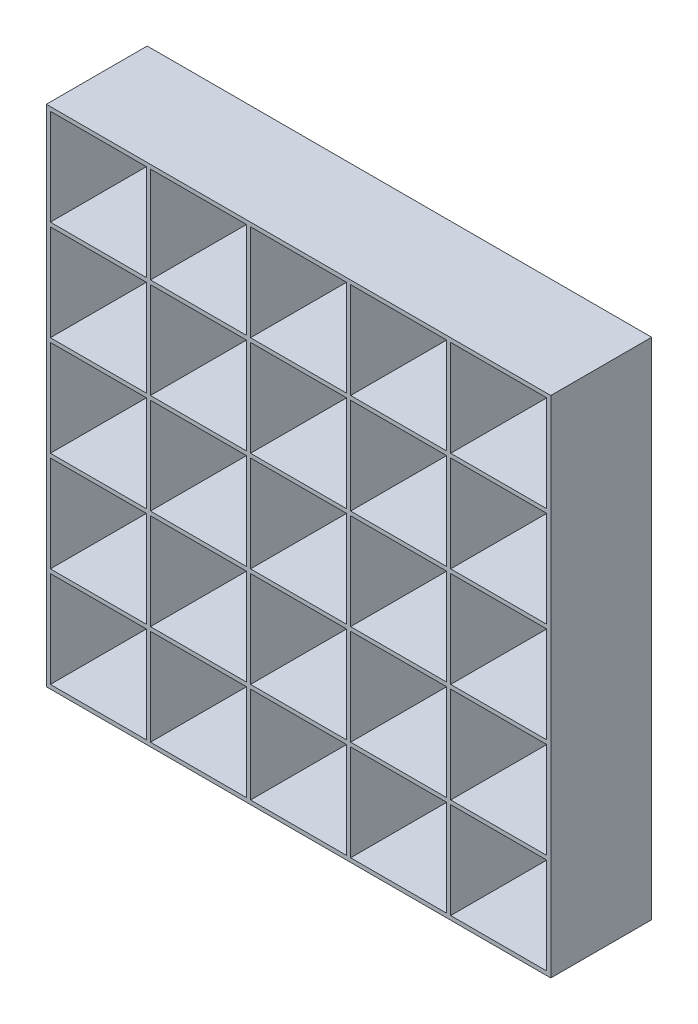
SolidWorks part; units mm, degrees
ref_plane "Front Plane" through (0, 0, 0) normal (0, 0, 1) x (1, 0, 0)
ref_plane "Top Plane" through (0, 0, 0) normal (0, 1, 0) x (1, 0, 0)
ref_plane "Right Plane" through (0, 0, 0) normal (1, 0, 0) x (0, 0, -1)
sketch "Sketch1" plane through (0, 0, 0) normal (0, 0, 1) x (1, 0, 0)
  line L1 (1250, 1250) -> (-1250, 1250)
  line L2 (1250, 1250) -> (1250, -1250)
  line L3 (1250, -1250) -> (-1250, -1250)
  line L4 (-1250, 1250) -> (-1250, -1250)
  line L5 (1250, 1250) -> (-1250, -1250) construction
  line L6 (1250, -1250) -> (-1250, 1250) construction
  line L7 (-1250, 1250) -> (-1230, 1250)
  line L8 (-1250, 1250) -> (-1250, -1250)
  line L9 (-1250, -1250) -> (-1230, -1250)
  line L10 (-1230, 1250) -> (-1230, -1250)
  point P0 (0, 0)
  dimension "D1" = 2500
  dimension "D2" = 2500
  dimension "D3" = 20
extrude "Boss-Extrude1" add sketch "Sketch1" along normal blind 500 contours L4 L3 L2 L1
sketch "Sketch3" plane through (0, 0, 500) normal (0, 0, 1) x (1, 0, 0)
  line L0 (-734, -1170.8048) -> (-734, -1230)
  line L109 (-1230, 1230) -> (-1230, 754)
  line L117 (-734, -238) -> (-258, -238)
  line L120 (-1230, 1230) -> (-754, 1230)
  line L126 (1230, 1230) -> (1230, 754)
  line L130 (-734, -1230) -> (-258, -1230)
  line L132 (-1230, 1230) -> (-754, 1230)
  line L133 (-1230, 1230) -> (-1230, 754)
  line L134 (-1230, 754) -> (-754, 754)
  line L135 (-754, 1230) -> (-754, 774.8128)
  line L137 (-754, 1230) -> (-754, 754)
  line L139 (-734, 1230) -> (-734, 754)
  line L140 (-1230, 754) -> (-754, 754)
  line L142 (-1230, 734) -> (-754, 734)
  line L144 (-1230, 734) -> (-754, 734)
  line L145 (-1230, 734) -> (-1230, 258)
  line L146 (-1230, 258) -> (-754, 258)
  line L147 (-754, 734) -> (-754, 258)
  line L148 (-1230, 258) -> (-754, 258)
  line L150 (-1230, 238) -> (-754, 238)
  line L152 (-1230, 238) -> (-754, 238)
  line L153 (-1230, 238) -> (-1230, -238)
  line L154 (-1230, -238) -> (-751.9983, -238)
  line L155 (-754, 238) -> (-754, -238)
  line L156 (-1230, -258) -> (-754, -258)
  line L158 (-1230, -258) -> (-754, -258)
  line L159 (-1230, -258) -> (-1230, -734)
  line L160 (-1230, -734) -> (-754, -734)
  line L161 (-754, -258) -> (-754, -734)
  line L162 (-1230, -734) -> (-754, -734)
  line L164 (-1230, -754) -> (-754, -754)
  line L166 (-1230, -754) -> (-754, -754)
  line L167 (-1230, -754) -> (-1230, -1230)
  line L168 (-1230, -1230) -> (-754, -1230)
  line L169 (-754, -754) -> (-754, -1230)
  line L170 (-734, 734) -> (-258, 734)
  line L171 (-734, 1230) -> (-258, 1230)
  line L172 (-734, 1230) -> (-734, 754)
  line L173 (-734, 754) -> (-258, 754)
  line L174 (-258, 1230) -> (-258, 754)
  line L176 (-258, 1230) -> (-258, 754)
  line L178 (-238, 1230) -> (-238, 754)
  line L179 (-238, 1230) -> (238, 1230)
  line L180 (-238, 1230) -> (-238, 754)
  line L181 (-238, 754) -> (238, 754)
  line L182 (238, 1230) -> (238, 754)
  line L184 (238, 1230) -> (238, 754)
  line L186 (258, 1230) -> (258, 754)
  line L187 (258, 1230) -> (734, 1230)
  line L188 (258, 1230) -> (258, 754)
  line L189 (258, 754) -> (734, 754)
  line L190 (734, 1230) -> (734, 754)
  line L192 (734, 1230) -> (734, 754)
  line L194 (754, 1230) -> (754, 754)
  line L195 (-734, 754) -> (-258, 754)
  line L196 (-734, 734) -> (-734, 258)
  line L197 (-754, 734) -> (-754, 258)
  line L198 (-238, 754) -> (238, 754)
  line L199 (-238, 734) -> (238, 734)
  line L200 (-258, 734) -> (-258, 258)
  line L201 (-238, 734) -> (-238, 258)
  line L202 (258, 754) -> (734, 754)
  line L203 (258, 734) -> (734, 734)
  line L204 (238, 734) -> (238, 258)
  line L205 (258, 734) -> (258, 258)
  line L206 (734, 734) -> (734, 258)
  line L207 (754, 734) -> (754, 258)
  line L208 (754, 754) -> (1230, 754)
  line L209 (754, 734) -> (1230, 734)
  line L210 (1230, 734) -> (1230, 258)
  line L211 (-734, 1230) -> (-258, 1230)
  line L212 (-238, 1230) -> (238, 1230)
  line L213 (258, 1230) -> (734, 1230)
  line L214 (754, 1230) -> (1230, 1230)
  line L215 (-1230, 734) -> (-1230, 258)
  line L216 (-1230, 238) -> (-1230, -238)
  line L217 (-1230, -258) -> (-1230, -734)
  line L218 (-754, -258) -> (-754, -734)
  line L219 (-734, -258) -> (-258, -258)
  line L220 (-734, 258) -> (-258, 258)
  line L221 (-734, 238) -> (-258, 238)
  line L222 (-734, 238) -> (-734, -238)
  line L223 (-754, 238) -> (-754, -238)
  line L224 (-238, 258) -> (238, 258)
  line L225 (-238, 238) -> (238, 238)
  line L226 (-258, 238) -> (-258, -238)
  line L227 (-238, 238) -> (-238, -238)
  line L228 (-238, -238) -> (238, -238)
  line L229 (-238, -258) -> (238, -258)
  line L230 (-258, -258) -> (-258, -734)
  line L231 (-238, -238) -> (-216.5673, -238)
  line L232 (-734, -258) -> (-734, -734)
  line L233 (-238, -258) -> (-238, -734)
  line L234 (238, -258) -> (238, -734)
  line L235 (258, -258) -> (258, -734)
  line L236 (258, -238) -> (734, -238)
  line L237 (258, -258) -> (734, -258)
  line L238 (734, -258) -> (734, -734)
  line L239 (754, -258) -> (754, -734)
  line L240 (754, -238) -> (1230, -238)
  line L241 (754, -258) -> (1230, -258)
  line L242 (1230, -258) -> (1230, -734)
  line L243 (1230, 238) -> (1230, -238)
  line L244 (734, 238) -> (734, -238)
  line L245 (754, 238) -> (754, -238)
  line L246 (754, 258) -> (1230, 258)
  line L247 (754, 238) -> (1230, 238)
  line L248 (258, 258) -> (734, 258)
  line L249 (258, 238) -> (734, 238)
  line L250 (258, 238) -> (258, -238)
  line L251 (238, 238) -> (238, -238)
  line L252 (-734, 258) -> (-680.3174, 258)
  line L253 (238, -754) -> (238, -1230)
  line L254 (-238, -1230) -> (238, -1230)
  line L255 (258, -1230) -> (734, -1230)
  line L256 (754, -1230) -> (1230, -1230)
  line L257 (258, -754) -> (258, -1230)
  line L258 (258, -734) -> (734, -734)
  line L259 (258, -754) -> (734, -754)
  line L260 (754, -734) -> (1230, -734)
  line L261 (754, -754) -> (1230, -754)
  line L262 (734, -754) -> (734, -1230)
  line L263 (754, -754) -> (754, -1230)
  line L264 (1230, -754) -> (1230, -1230)
  line L265 (-1230, -754) -> (-1230, -1230)
  line L266 (-734, -734) -> (-258, -734)
  line L267 (-734, -754) -> (-258, -754)
  line L268 (-754, -754) -> (-754, -1170.8048)
  line L269 (-734, -754) -> (-734, -1170.8048)
  line L270 (-258, -754) -> (-258, -1230)
  line L271 (-238, -754) -> (-238, -1230)
  line L272 (-238, -734) -> (238, -734)
  line L273 (-238, -754) -> (238, -754)
extrude "Cut-Extrude2" cut sketch "Sketch3" against normal through all contours L137 L135 L120 L109 L134 | L147 L142 L145 L146 | L155 L150 L153 L154 | L174 L171 L139 L173 | L196 L220 L200 L170 | L226 L221 L222 L117 | L161 L156 L159 L160 | L232 L266 L230 L219 | L270 L267 L269 L0 L130 | L169 L164 L167 L168 | L273 L271 L254 L253 | L233 L272 L234 L229 | L251 L225 L227 L228 | L201 L224 L204 L199 | L182 L179 L178 L181 | L190 L187 L186 L189 | L205 L248 L206 L203 | L249 L250 L236 L244 | L235 L258 L238 L237 | L262 L259 L257 L255 | L264 L261 L263 L256 | L239 L260 L242 L241 | L247 L245 L240 L243 | L207 L246 L210 L209 | L214 L194 L208 L126
